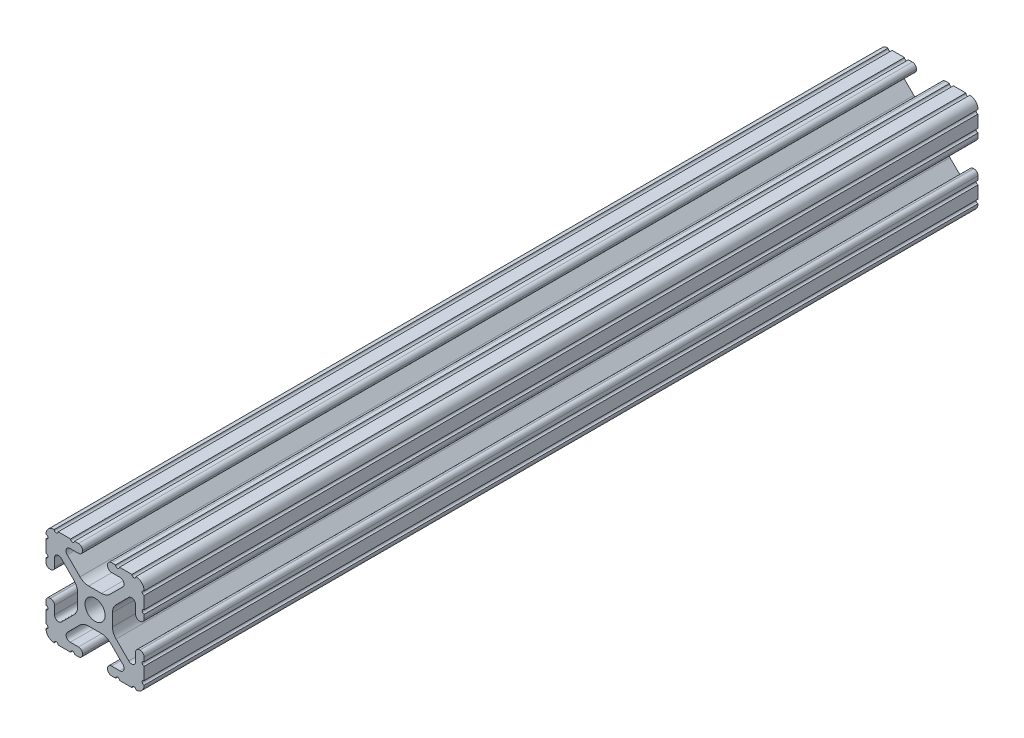
SolidWorks part; units mm, degrees
ref_plane "Front Plane" through (0, 0, 0) normal (0, 0, 1) x (1, 0, 0)
ref_plane "Top Plane" through (0, 0, 0) normal (0, 1, 0) x (1, 0, 0)
ref_plane "Right Plane" through (0, 0, 0) normal (1, 0, 0) x (0, 0, -1)
sketch "Sketch1" plane through (0, 0, 0) normal (0, 0, 1) x (1, 0, 0)
  line L88 (-7.1797, -8.6452) -> (-3.9523, -5.4237)
  line L89 (-1.7093, -4.4958) -> (1.7093, -4.4958)
  line L90 (3.9523, -5.4237) -> (7.1797, -8.6452)
  line L91 (6.4164, -10.4902) -> (4.2875, -10.4902)
  line L92 (3.2385, -11.5392) -> (3.2385, -11.651)
  line L93 (4.2875, -12.7) -> (5.3171, -12.7)
  line L94 (6.3331, -12.7) -> (9.5504, -12.7)
  line L95 (12.7, -9.5504) -> (12.7, -6.3331)
  line L96 (12.7, -5.3171) -> (12.7, -4.2875)
  line L97 (11.651, -3.2385) -> (11.5392, -3.2385)
  line L98 (10.4902, -4.2875) -> (10.4902, -6.4021)
  line L99 (8.7371, -7.1294) -> (5.441, -3.8408)
  line L100 (4.5085, -1.5932) -> (4.5085, 1.5932)
  line L101 (5.441, 3.8408) -> (8.7371, 7.1294)
  line L102 (10.4902, 6.4021) -> (10.4902, 4.2875)
  line L103 (11.5392, 3.2385) -> (11.651, 3.2385)
  line L104 (12.7, 4.2875) -> (12.7, 5.3171)
  line L105 (12.7, 6.3331) -> (12.7, 9.5504)
  line L106 (9.5504, 12.7) -> (6.3331, 12.7)
  line L107 (5.3171, 12.7) -> (4.2875, 12.7)
  line L108 (3.2385, 11.651) -> (3.2385, 11.5392)
  line L109 (4.2875, 10.4902) -> (6.4768, 10.4902)
  line L110 (7.207, 8.7244) -> (3.8983, 5.4232)
  line L111 (1.6558, 4.4958) -> (-1.6558, 4.4958)
  line L112 (-3.8983, 5.4232) -> (-7.207, 8.7244)
  line L113 (-6.4768, 10.4902) -> (-4.2875, 10.4902)
  line L114 (-3.2385, 11.5392) -> (-3.2385, 11.651)
  line L115 (-4.2875, 12.7) -> (-5.3171, 12.7)
  line L116 (-6.3331, 12.7) -> (-9.5504, 12.7)
  line L117 (-12.7, 9.5504) -> (-12.7, 6.3331)
  line L118 (-12.7, 5.3171) -> (-12.7, 4.2875)
  line L119 (-11.651, 3.2385) -> (-11.5392, 3.2385)
  line L120 (-10.4902, 4.2875) -> (-10.4902, 6.4021)
  line L121 (-8.7371, 7.1294) -> (-5.441, 3.8408)
  line L122 (-4.5085, 1.5932) -> (-4.5085, -1.5932)
  line L123 (-5.441, -3.8408) -> (-8.7371, -7.1294)
  line L124 (-10.4902, -6.4021) -> (-10.4902, -4.2875)
  line L125 (-11.5392, -3.2385) -> (-11.651, -3.2385)
  line L126 (-12.7, -4.2875) -> (-12.7, -5.3171)
  line L127 (-12.7, -6.3331) -> (-12.7, -9.5504)
  line L128 (-9.5504, -12.7) -> (-6.3331, -12.7)
  line L129 (-5.3171, -12.7) -> (-4.2875, -12.7)
  line L130 (-3.2385, -11.651) -> (-3.2385, -11.5392)
  line L131 (-4.2875, -10.4902) -> (-6.4164, -10.4902)
  circle A1 centre (0, 0) radius 2.6035
  arc A104 (-7.1797, -8.6452) -> (-6.4164, -10.4902) centre (-6.4164, -9.4098) ccw
  arc A105 (-1.7093, -4.4958) -> (-3.9523, -5.4237) centre (-1.7093, -7.6708) ccw
  arc A106 (3.9523, -5.4237) -> (1.7093, -4.4958) centre (1.7093, -7.6708) ccw
  arc A107 (6.4164, -10.4902) -> (7.1797, -8.6452) centre (6.4164, -9.4098) ccw
  arc A108 (4.2875, -10.4902) -> (3.2385, -11.5392) centre (4.2875, -11.5392) ccw
  arc A109 (3.2385, -11.651) -> (4.2875, -12.7) centre (4.2875, -11.651) ccw
  arc A110 (6.3331, -12.7) -> (5.3171, -12.7) centre (5.8251, -12.7) ccw
  arc A111 (10.5664, -12.6998) -> (9.5504, -12.7) centre (10.0584, -12.7) ccw
  arc A112 (10.5664, -12.6998) -> (12.6998, -10.5664) centre (10.5918, -10.5918) ccw
  arc A113 (12.7, -9.5504) -> (12.6998, -10.5664) centre (12.7, -10.0584) ccw
  arc A114 (12.7, -5.3171) -> (12.7, -6.3331) centre (12.7, -5.8251) ccw
  arc A115 (12.7, -4.2875) -> (11.651, -3.2385) centre (11.651, -4.2875) ccw
  arc A116 (11.5392, -3.2385) -> (10.4902, -4.2875) centre (11.5392, -4.2875) ccw
  arc A117 (8.7371, -7.1294) -> (10.4902, -6.4021) centre (9.4628, -6.4021) ccw
  arc A118 (4.5085, -1.5932) -> (5.441, -3.8408) centre (7.6835, -1.5932) ccw
  arc A119 (5.441, 3.8408) -> (4.5085, 1.5932) centre (7.6835, 1.5932) ccw
  arc A120 (10.4902, 6.4021) -> (8.7371, 7.1294) centre (9.4628, 6.4021) ccw
  arc A121 (10.4902, 4.2875) -> (11.5392, 3.2385) centre (11.5392, 4.2875) ccw
  arc A122 (11.651, 3.2385) -> (12.7, 4.2875) centre (11.651, 4.2875) ccw
  arc A123 (12.7, 6.3331) -> (12.7, 5.3171) centre (12.7, 5.8251) ccw
  arc A124 (12.6998, 10.5664) -> (12.7, 9.5504) centre (12.7, 10.0584) ccw
  arc A125 (12.6998, 10.5664) -> (10.5664, 12.6998) centre (10.5918, 10.5918) ccw
  arc A126 (9.5504, 12.7) -> (10.5664, 12.6998) centre (10.0584, 12.7) ccw
  arc A127 (5.3171, 12.7) -> (6.3331, 12.7) centre (5.8251, 12.7) ccw
  arc A128 (4.2875, 12.7) -> (3.2385, 11.651) centre (4.2875, 11.651) ccw
  arc A129 (3.2385, 11.5392) -> (4.2875, 10.4902) centre (4.2875, 11.5392) ccw
  arc A130 (7.207, 8.7244) -> (6.4768, 10.4902) centre (6.4768, 9.4563) ccw
  arc A131 (1.6558, 4.4958) -> (3.8983, 5.4232) centre (1.6558, 7.6708) ccw
  arc A132 (-3.8983, 5.4232) -> (-1.6558, 4.4958) centre (-1.6558, 7.6708) ccw
  arc A133 (-6.4768, 10.4902) -> (-7.207, 8.7244) centre (-6.4768, 9.4563) ccw
  arc A134 (-4.2875, 10.4902) -> (-3.2385, 11.5392) centre (-4.2875, 11.5392) ccw
  arc A135 (-3.2385, 11.651) -> (-4.2875, 12.7) centre (-4.2875, 11.651) ccw
  arc A136 (-6.3331, 12.7) -> (-5.3171, 12.7) centre (-5.8251, 12.7) ccw
  arc A137 (-10.5664, 12.6998) -> (-9.5504, 12.7) centre (-10.0584, 12.7) ccw
  arc A138 (-10.5664, 12.6998) -> (-12.6998, 10.5664) centre (-10.5918, 10.5918) ccw
  arc A139 (-12.7, 9.5504) -> (-12.6998, 10.5664) centre (-12.7, 10.0584) ccw
  arc A140 (-12.7, 5.3171) -> (-12.7, 6.3331) centre (-12.7, 5.8251) ccw
  arc A141 (-12.7, 4.2875) -> (-11.651, 3.2385) centre (-11.651, 4.2875) ccw
  arc A142 (-11.5392, 3.2385) -> (-10.4902, 4.2875) centre (-11.5392, 4.2875) ccw
  arc A143 (-8.7371, 7.1294) -> (-10.4902, 6.4021) centre (-9.4628, 6.4021) ccw
  arc A144 (-4.5085, 1.5932) -> (-5.441, 3.8408) centre (-7.6835, 1.5932) ccw
  arc A145 (-5.441, -3.8408) -> (-4.5085, -1.5932) centre (-7.6835, -1.5932) ccw
  arc A146 (-10.4902, -6.4021) -> (-8.7371, -7.1294) centre (-9.4628, -6.4021) ccw
  arc A147 (-10.4902, -4.2875) -> (-11.5392, -3.2385) centre (-11.5392, -4.2875) ccw
  arc A148 (-11.651, -3.2385) -> (-12.7, -4.2875) centre (-11.651, -4.2875) ccw
  arc A149 (-12.7, -6.3331) -> (-12.7, -5.3171) centre (-12.7, -5.8251) ccw
  arc A150 (-12.6998, -10.5664) -> (-12.7, -9.5504) centre (-12.7, -10.0584) ccw
  arc A151 (-12.6998, -10.5664) -> (-10.5664, -12.6998) centre (-10.5918, -10.5918) ccw
  arc A152 (-9.5504, -12.7) -> (-10.5664, -12.6998) centre (-10.0584, -12.7) ccw
  arc A153 (-5.3171, -12.7) -> (-6.3331, -12.7) centre (-5.8251, -12.7) ccw
  arc A154 (-4.2875, -12.7) -> (-3.2385, -11.651) centre (-4.2875, -11.651) ccw
  arc A155 (-3.2385, -11.5392) -> (-4.2875, -10.4902) centre (-4.2875, -11.5392) ccw
extrude "Boss-Extrude1" add sketch "Sketch1" along normal mid plane 215.9
